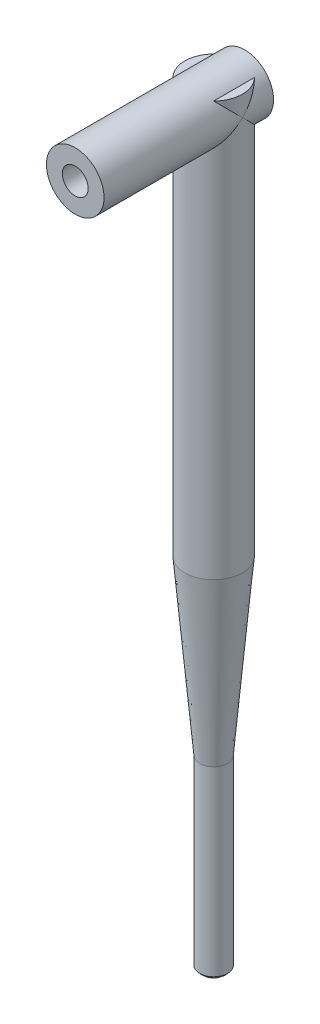
SolidWorks part; units mm, degrees
ref_plane "Front Plane" through (0, 0, 0) normal (0, 0, 1) x (1, 0, 0)
ref_plane "Top Plane" through (0, 0, 0) normal (0, 1, 0) x (1, 0, 0)
ref_plane "Right Plane" through (0, 0, 0) normal (1, 0, 0) x (0, 0, -1)
sketch "Sketch1" plane through (0, 0, 0) normal (1, 0, 0) x (0, 0, -1)
  line L0 (0, 4.6) -> (0, -170.4)
  line L3 (-6.5, -88.9) -> (-6.5, 4.6)
  line L4 (-6.5, 4.6) -> (0, 4.6)
  line L5 (-3.14, -168.8131) -> (-3.14, -127.8131)
  line L6 (-3.14, -127.8131) -> (-6.5, -88.9)
  arc A0 (-3.14, -168.8131) -> (0, -170.4) centre (0, -166.5) ccw
  dimension "D1" = 175
  dimension "D3" = 3.9
  dimension "D2" = 6.5
  dimension "D4" = 93.5
  dimension "D5" = 4.6
  dimension "D6" = 41
  dimension "D7" = 3.14
revolve "Revolve1" add sketch "Sketch1" angle 360 about L0
sketch "Sketch2" plane through (0, 0, 0) normal (0, 0, 1) x (1, 0, 0)
  line L0 (6.5, -88.9) -> (6.5, 4.6) construction
  circle A0 centre (0, 0) radius 6.5
extrude "Boss-Extrude1" add sketch "Sketch2" along normal blind 31.22 and the other way blind 7
sketch "Sketch3" plane through (0, 0, 31.22) normal (0, 0, 1) x (1, 0, 0)
  circle A0 centre (0, 0) radius 2.9189
extrude "Cut-Extrude1" cut sketch "Sketch3" against normal blind 8.36
